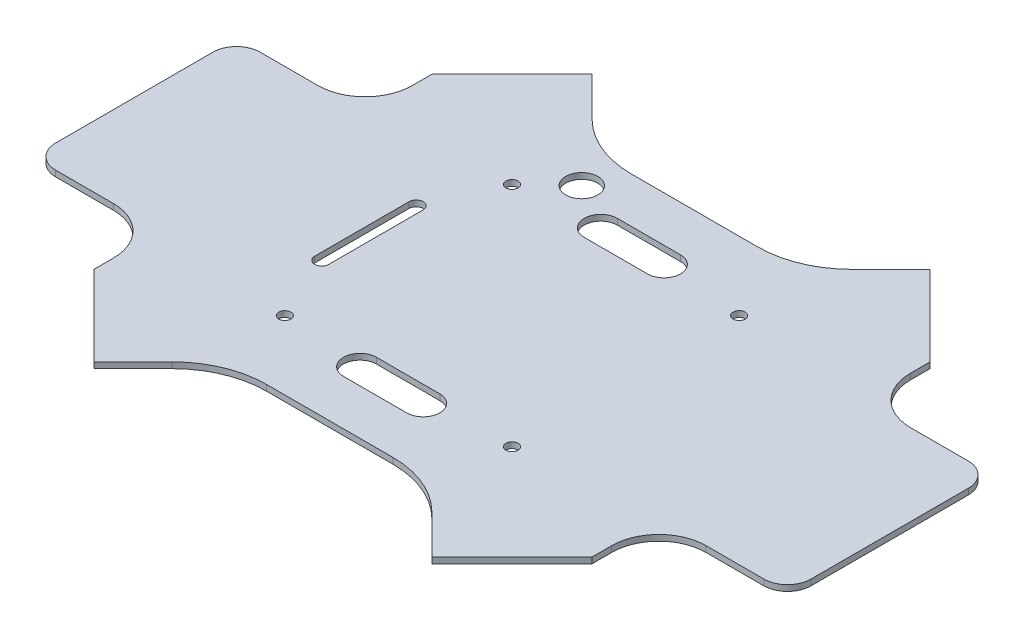
SolidWorks part; units mm, degrees
material "Thornel Mat VMA"
ref_plane "Front Plane" through (0, 0, 0) normal (0, 0, 1) x (1, 0, 0)
ref_plane "Top Plane" through (0, 0, 0) normal (0, 1, 0) x (1, 0, 0)
ref_plane "Right Plane" through (0, 0, 0) normal (1, 0, 0) x (0, 0, -1)
sketch "Sketch1" plane through (0, 0, 0) normal (0, 1, 0) x (1, 0, 0)
  line L1 (-101.6, -76.2) -> (101.6, -76.2)
  line L2 (-101.6, -76.2) -> (-101.6, 76.2)
  line L3 (-101.6, 76.2) -> (101.6, 76.2)
  line L4 (101.6, -76.2) -> (101.6, 76.2)
  line L5 (-101.6, -76.2) -> (101.6, 76.2) construction
  line L6 (-101.6, 76.2) -> (101.6, -76.2) construction
  point P0 (0, 0)
  dimension "D1" = 203.2
  dimension "D2" = 152.4
extrude "Boss-Extrude1" add sketch "Sketch1" along normal mid plane 1.5875
sketch "Centering Sketch" plane through (0, 0.7937, 0) normal (0, 1, 0) x (1, 0, 0)
  line L0 (101.6, 76.2) -> (-101.6, 76.2) construction
  line L1 (-76.2, -76.2) -> (76.2, -76.2)
  line L2 (-76.2, -76.2) -> (-76.2, 76.2)
  line L3 (-76.2, 76.2) -> (76.2, 76.2)
  line L4 (76.2, -76.2) -> (76.2, 76.2)
  line L5 (-76.2, -76.2) -> (76.2, 76.2) construction
  line L6 (-76.2, 76.2) -> (76.2, -76.2) construction
  point P0 (0, 0)
  dimension "D1" = 152.4
sketch "Sketch2" plane through (0, 0.7937, 0) normal (0, 1, 0) x (1, 0, 0)
  line L0 (0, -76.2) -> (0, 76.2) construction
  line L1 (-101.6, -76.2) -> (101.6, -76.2) construction
  line L2 (101.6, 76.2) -> (-101.6, 76.2) construction
  line L3 (-101.6, 0) -> (101.6, 0) construction
  line L4 (-101.6, 76.2) -> (-101.6, -76.2) construction
  line L5 (101.6, -76.2) -> (101.6, 76.2) construction
  line L6 (-101.6, 76.2) -> (101.6, 76.2)
  line L7 (67.0131, 27.5) -> (101.6, 27.5)
  line L8 (27.5, -49.0526) -> (45.4605, -67.0131)
  line L9 (45.4605, -67.0131) -> (67.0131, -45.4605)
  line L10 (67.0131, -27.5) -> (67.0131, -45.4605)
  line L11 (27.5, 49.0526) -> (-27.5, 49.0526)
  line L12 (27.5, -49.0526) -> (-27.5, -49.0526)
  line L13 (67.0131, -27.5) -> (101.6, -27.5)
  line L14 (101.6, -27.5) -> (101.6, 27.5)
  line L15 (67.0131, 27.5) -> (67.0131, 45.4605)
  line L16 (45.4605, 67.0131) -> (67.0131, 45.4605)
  line L17 (27.5, 49.0526) -> (45.4605, 67.0131)
  line L18 (-45.4605, -67.0131) -> (-67.0131, -45.4605)
  line L19 (-27.5, -49.0526) -> (-45.4605, -67.0131)
  line L20 (-27.5, 49.0526) -> (-45.4605, 67.0131)
  line L21 (-45.4605, 67.0131) -> (-67.0131, 45.4605)
  line L22 (-67.0131, 27.5) -> (-67.0131, 45.4605)
  line L23 (-101.6, -27.5) -> (-101.6, 27.5)
  line L24 (-67.0131, -27.5) -> (-101.6, -27.5)
  line L25 (-67.0131, -27.5) -> (-67.0131, -45.4605)
  line L26 (-67.0131, 27.5) -> (-101.6, 27.5)
  line L32 (-101.6, 76.2) -> (-101.6, -76.2)
  line L33 (-101.6, -76.2) -> (101.6, -76.2)
  line L34 (101.6, 76.2) -> (101.6, -76.2)
  point P22 (0, 49.0526)
  point P32 (0, -49.0526)
  dimension "D1" = 27.5
  dimension "D2" = 17.9605
  dimension "D3" = 27.1474
extrude "Cut-Extrude1" cut sketch "Sketch2" against normal through all
fillet "Fillet1" radius 25.4 4 edges at (27.5, 0, -49.0526) (-27.5, 0, -49.0526) (-27.5, 0, 49.0526) (27.5, 0, 49.0526)
fillet "Fillet2" radius 12.7 4 edges at (67.0131, 0, 27.5) (-67.0131, 0, 27.5) (-67.0131, 0, -27.5) (67.0131, 0, -27.5)
fillet "Fillet3" radius 6.35 4 edges at (101.6, 0, 27.5) (-101.6, 0, 27.5) (-101.6, 0, -27.5) (101.6, 0, -27.5)
sketch "Sketch3" plane through (0, 0.7937, 0) normal (0, 1, 0) x (1, 0, 0)
  line L0 (8.509, 32.385) -> (-8.509, 32.385) construction
  line L1 (8.509, 36.83) -> (-8.509, 36.83)
  line L2 (8.509, 27.94) -> (-8.509, 27.94)
  line L3 (101.6, -21.15) -> (101.6, 21.15) construction
  line L4 (0, 0) -> (101.6, 0) construction
  line L8 (8.509, -32.385) -> (-8.509, -32.385) construction
  line L9 (8.509, -36.83) -> (-8.509, -36.83)
  line L10 (8.509, -27.94) -> (-8.509, -27.94)
  arc A0 (8.509, 36.83) -> (8.509, 27.94) centre (8.509, 32.385) cw
  arc A1 (-8.509, 27.94) -> (-8.509, 36.83) centre (-8.509, 32.385) cw
  arc A4 (8.509, -36.83) -> (8.509, -27.94) centre (8.509, -32.385) ccw
  arc A5 (-8.509, -27.94) -> (-8.509, -36.83) centre (-8.509, -32.385) ccw
  point P2 (0, 32.385)
  point P21 (0, -32.385)
  dimension "D5" = 8.89
  dimension "D6" = 17.018
  dimension "D8" = 27.94
extrude "ESC Wiring Slots" cut sketch "Sketch3" against normal up to next contours L10 A5 L9 A4
sketch "Sketch4" plane through (0, 0.7937, 0) normal (0, 1, 0) x (1, 0, 0)
  line L0 (0, 49.0526) -> (0, -49.0526) construction
  line L1 (16.979, 49.0526) -> (-16.979, 49.0526) construction
  line L2 (16.979, -49.0526) -> (-16.979, -49.0526) construction
  line L3 (-38.481, 12.7) -> (-38.481, -12.7) construction
  line L4 (-36.576, 12.7) -> (-36.576, -12.7)
  line L5 (-40.386, 12.7) -> (-40.386, -12.7)
  line L6 (0, 0) -> (-101.6, 0) construction
  line L7 (-101.6, 21.15) -> (-101.6, -21.15) construction
  arc A0 (-36.576, 12.7) -> (-40.386, 12.7) centre (-38.481, 12.7) ccw
  arc A1 (-40.386, -12.7) -> (-36.576, -12.7) centre (-38.481, -12.7) ccw
  point P8 (-38.481, 0)
  dimension "D1" = 63.119
  dimension "D2" = 3.81
  dimension "D3" = 25.4
extrude "PM, Telemetry, & Camera Wire Slots" cut sketch "Sketch4" against normal up to next
sketch "Sketch5" plane through (0, 0.7937, 0) normal (0, 1, 0) x (1, 0, 0)
  line L0 (16.979, 49.0526) -> (-16.979, 49.0526) construction
  circle A0 centre (-20.8825, 39.6546) radius 4.318
  arc A1 (-8.509, 36.83) -> (-8.509, 27.94) centre (-8.509, 32.385) ccw construction
  dimension "D1" = 8.636
  dimension "D2" = 5.08
  dimension "D3" = 5.588
extrude "Safety Switch Hole" cut sketch "Sketch5" against normal up to next
hole_wizard "#4 Clearance Hole (Standoff Screws)" positions "Sketch8" profile "Sketch9" hole size "#4" standard "ANSI Inch" end condition up to next
sketch "Sketch8" plane through (0, 0.7937, 0) normal (0, 1, 0) x (1, 0, 0)
  line L0 (0, 0) -> (0, -49.0526) construction
  line L1 (16.979, -49.0526) -> (-16.979, -49.0526) construction
  line L3 (0, 0) -> (-101.6, 0) construction
  line L4 (-101.6, 21.15) -> (-101.6, -21.15) construction
  line L7 (-45.4605, -67.0131) -> (-67.0131, -45.4605) construction
  line L9 (-14.8465, -61.7061) -> (-50.9494, -25.6032) construction
  line L10 (0, -25.6032) -> (-50.9494, -25.6032) construction
  line L11 (-56.2368, -56.2368) -> (-38.2763, -38.2763) construction
  line L13 (-38.2763, -38.2763) -> (-25.6032, -25.6032) construction
  point P0 (-30.5562, -30.5562)
  point P42 (30.5562, -30.5562)
  point P44 (30.5562, 30.5562)
  point P45 (-30.5562, 30.5562)
  dimension "D3" = 4.953
  dimension "D1" = 25.4
  dimension "D2" = 25.6032
sketch "Sketch9" plane through (-30.5562, 0.7937, 30.5562) normal (1, 0, 0) x (0, 0, 1)
  line L0 (0, 0) -> (0, 1.5875)
  line L1 (0, 1.5875) -> (1.6319, 1.5875)
  line L2 (1.6319, 1.5875) -> (1.6319, 0)
  line L5 (1.6319, 0) -> (0, 0)
  line L11 (0, -6.35) -> (0, 107.95) construction
  dimension "Thru Hole Dia." = 3.2639
  dimension "Thru Hole Depth" = 1.5875
